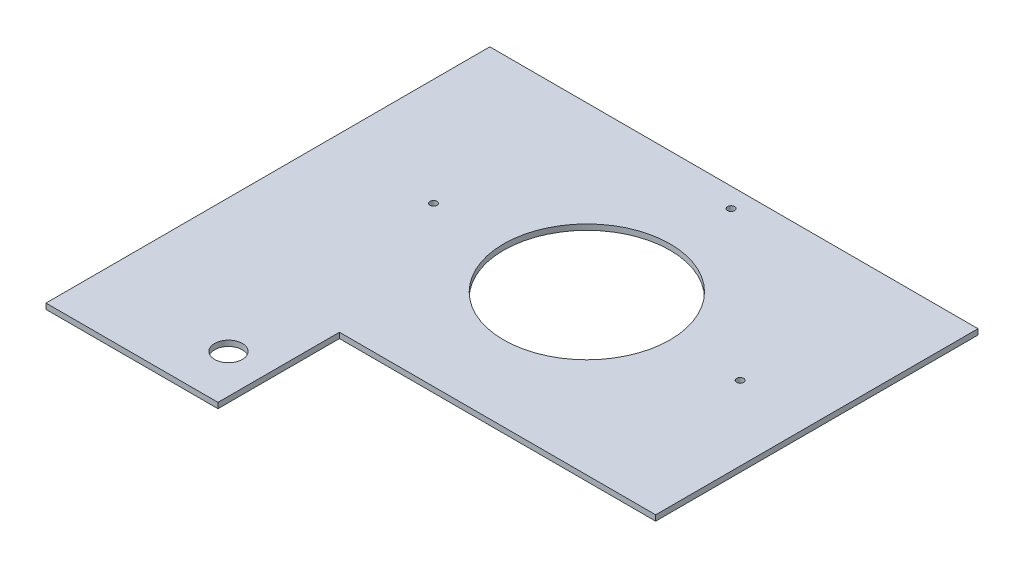
SolidWorks part; units mm, degrees
ref_plane "Alzado" through (0, 0, 0) normal (0, 0, 1) x (1, 0, 0)
ref_plane "Planta" through (0, 0, 0) normal (0, 1, 0) x (1, 0, 0)
ref_plane "Vista lateral" through (0, 0, 0) normal (1, 0, 0) x (0, 0, -1)
sketch "Croquis2" plane through (0, 0, 0) normal (0, 1, 0) x (1, 0, 0)
  line L0 (-164.0241, 177.5689) -> (-164.0241, -142.4311)
  line L4 (275.9759, 177.5689) -> (275.9759, -112.9585)
  line L31 (-9.0241, -112.9585) -> (275.9759, -112.9585)
  line L40 (275.9759, 177.5689) -> (-164.0241, 177.5689)
  line L43 (-79.0241, -112.9585) -> (-79.0241, 177.5689) construction
  line L46 (220.9759, 177.5689) -> (220.9759, -112.9585) construction
  line L48 (225.9759, 177.5689) -> (225.9759, -112.9585) construction
  line L49 (-164.0241, -142.4311) -> (-164.0241, -189.2567)
  line L52 (-164.0241, -189.2567) -> (-164.0241, -222.4267)
  line L53 (-164.0241, -222.4267) -> (-79.0241, -222.4267)
  line L58 (-9.0241, -112.9585) -> (-9.0241, -222.4267)
  line L60 (-79.0241, -222.4267) -> (-9.0241, -222.4267)
  circle A3 centre (70.9759, 30.0258) radius 75
  circle A28 centre (209.1759, 30.0258) radius 3.175
  circle A29 centre (-67.2241, 30.0258) radius 3.175
  circle A40 centre (70.9759, 160.0258) radius 3.175
  circle A41 centre (-44.0241, -177.9585) radius 12.5
  point P0 (70.9759, 30.0258)
  point P13 (70.9759, 30.0258)
  point P26 (73.475, 30.0258)
  point P29 (70.9759, 7.6644)
  point P51 (13.8491, 7.5952)
  point P54 (13.6242, 7.6644)
  point P68 (41.8242, 35.8644)
  dimension "D2" = 150
  dimension "D3" = 50
  dimension "D10" = 130
  dimension "D11" = 6.35
  dimension "D13" = 6.35
  dimension "D8" = 138.2
  dimension "D9" = 6.35
  dimension "D23" = 25
  dimension "D6" = 150
  dimension "D7" = 150
  dimension "D12" = 138.2
  dimension "D14" = 5
  dimension "D15" = 320
  dimension "D18" = 33.17
  dimension "D19" = 70
extrude "Saliente-Extruir2" add sketch "Croquis2" along normal blind 5
sketch "Croquis3" plane through (0, 5, 0) normal (0, 1, 0) x (1, 0, 0)
  point P0 (70.9759, 30.0258)
